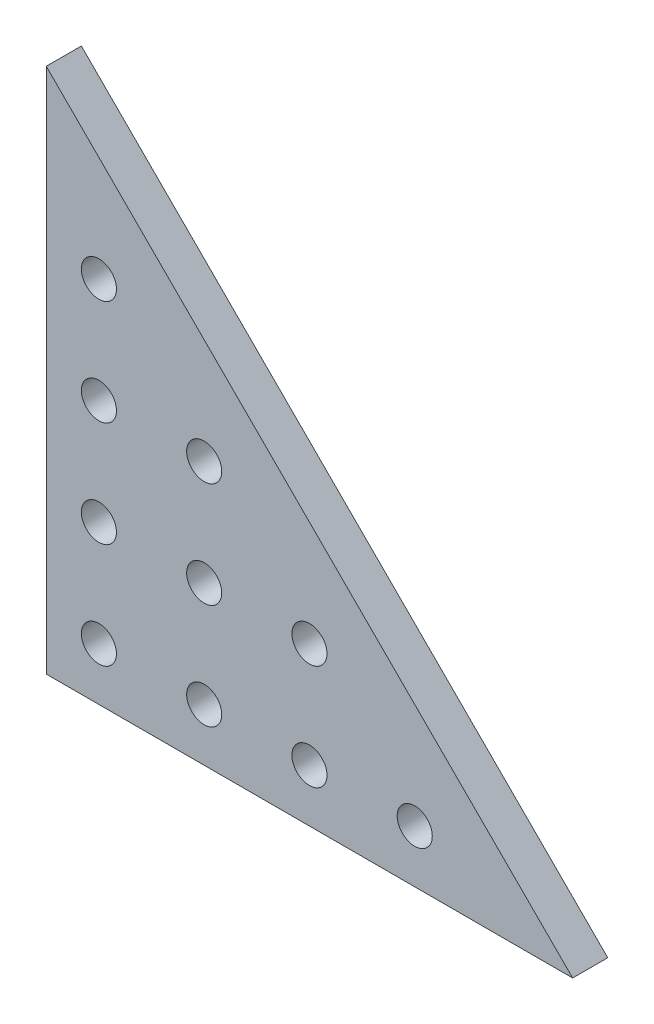
SolidWorks part; units mm, degrees
ref_plane "Alzado" through (0, 0, 0) normal (0, 0, 1) x (1, 0, 0)
ref_plane "Planta" through (0, 0, 0) normal (0, 1, 0) x (1, 0, 0)
ref_plane "Vista lateral" through (0, 0, 0) normal (1, 0, 0) x (0, 0, -1)
sketch "Model" plane through (0, 0, 0) normal (0, 0, 1) x (1, 0, 0)
  line L0 (-105.9434, 105.5565) -> (-105.9434, 60.5565)
  line L1 (-105.9434, 60.5565) -> (-60.9434, 60.5565)
  line L2 (-105.9434, 105.5565) -> (-60.9434, 60.5565)
  circle A0 centre (-101.4434, 92.0565) radius 1.5
  circle A1 centre (-101.4434, 83.0565) radius 1.5
  circle A2 centre (-92.4434, 83.0565) radius 1.5
  circle A3 centre (-101.4434, 74.0565) radius 1.5
  circle A4 centre (-92.4434, 74.0565) radius 1.5
  circle A5 centre (-83.4434, 74.0565) radius 1.5
  circle A6 centre (-101.4434, 65.0565) radius 1.5
  circle A7 centre (-92.4434, 65.0565) radius 1.5
  circle A8 centre (-83.4434, 65.0565) radius 1.5
  circle A9 centre (-74.4434, 65.0565) radius 1.5
extrude "Saliente-Extruir1" add sketch "Model" along normal blind 3
